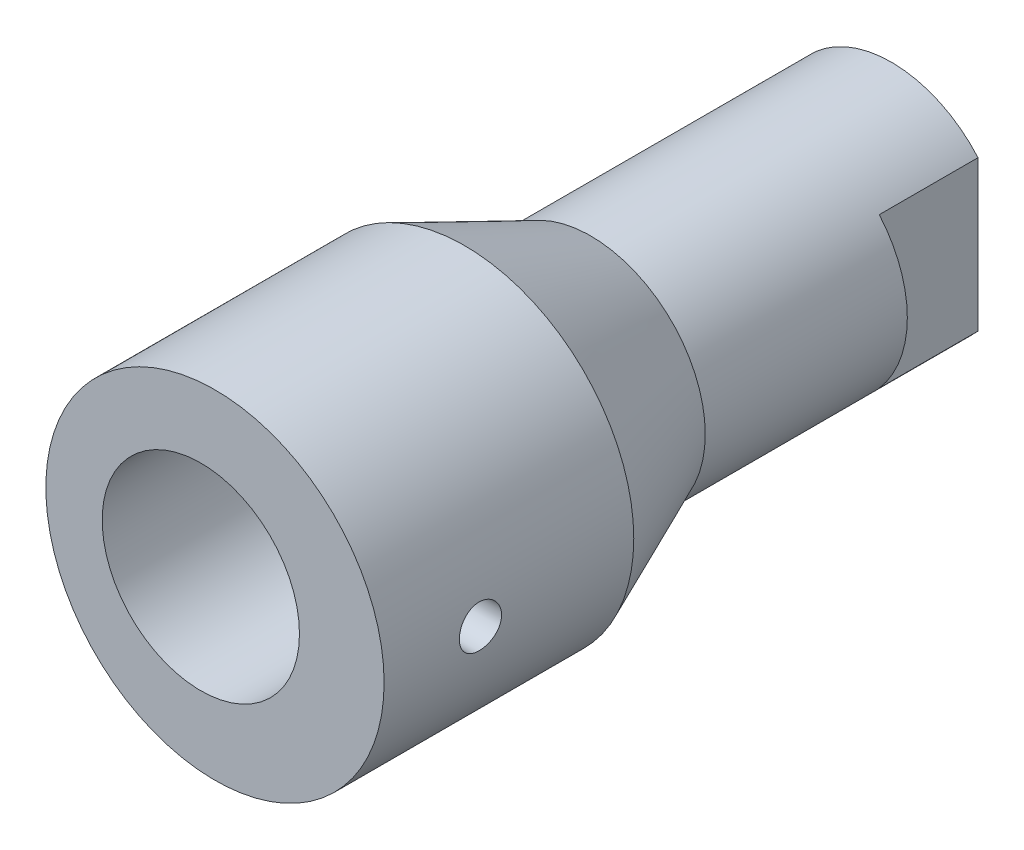
SolidWorks part; units mm, degrees
ref_plane "Ön Düzlem" through (0, 0, 0) normal (0, 0, 1) x (1, 0, 0)
ref_plane "Üst Düzlem" through (0, 0, 0) normal (0, 1, 0) x (1, 0, 0)
ref_plane "Sağ Düzlem" through (0, 0, 0) normal (1, 0, 0) x (0, 0, -1)
sketch "Çizim1" plane through (0, 0, 0) normal (1, 0, 0) x (0, 0, -1)
  line L0 (-16.3461, 9.525) -> (-2.2861, 9.525)
  line L1 (-2.2861, 9.525) -> (4.8139, 6.45)
  line L2 (4.8139, 6.45) -> (21.7539, 6.45)
  line L9 (-16.3461, 9.525) -> (-16.3461, 0)
  line L10 (-16.3461, 0) -> (21.7539, 0)
  line L11 (21.7539, 0) -> (21.7539, 6.45)
  point P2 (0, 0)
  point P7 (0, 0)
  point P9 (0, 0)
  dimension "D1" = 38.1
  dimension "D2" = 6.45
  dimension "D3" = 9.525
  dimension "D4" = 14.06
  dimension "D5" = 16.94
  dimension "D6" = 3.075
revolve "Döndür2" add sketch "Çizim1" angle 360 about L10
sketch "Çizim2" plane through (0, 0, 0) normal (0, 1, 0) x (1, 0, 0)
  line L1 (6.45, 21.7539) -> (4.87, 21.7539)
  line L2 (6.45, 21.7539) -> (6.45, 16.1939)
  line L3 (6.45, 16.1939) -> (4.87, 16.1939)
  line L4 (4.87, 21.7539) -> (4.87, 16.1939)
  dimension "D1" = 1.58
  dimension "D2" = 5.56
extrude "Kes-Ekstrüzyon1" cut sketch "Çizim2" against normal mid plane 10
sketch "Çizim6" plane through (0, 0, 16.3461) normal (0, 0, 1) x (1, 0, 0)
  line L0 (-0.7967, 0) -> (9.5233, 0.179) construction
  circle A0 centre (-0.7967, 0) radius 5.555
  circle A1 centre (0, 0) radius 9.525 construction
  dimension "D2" = 11.11
  dimension "D1" = 10.32
extrude "Kes-Ekstrüzyon2" cut sketch "Çizim6" against normal blind 14.06
sketch "Çizim9" plane through (0, 0, 0) normal (1, 0, 0) x (0, 0, -1)
  line L0 (-16.3461, -9.525) -> (-2.2861, -9.525) construction
  circle A0 centre (-10.918, 0) radius 1.19
  dimension "D2" = 2.38
  dimension "D1" = 9.525
extrude "Kes-Ekstrüzyon3" cut sketch "Çizim9" along normal blind 14.06
